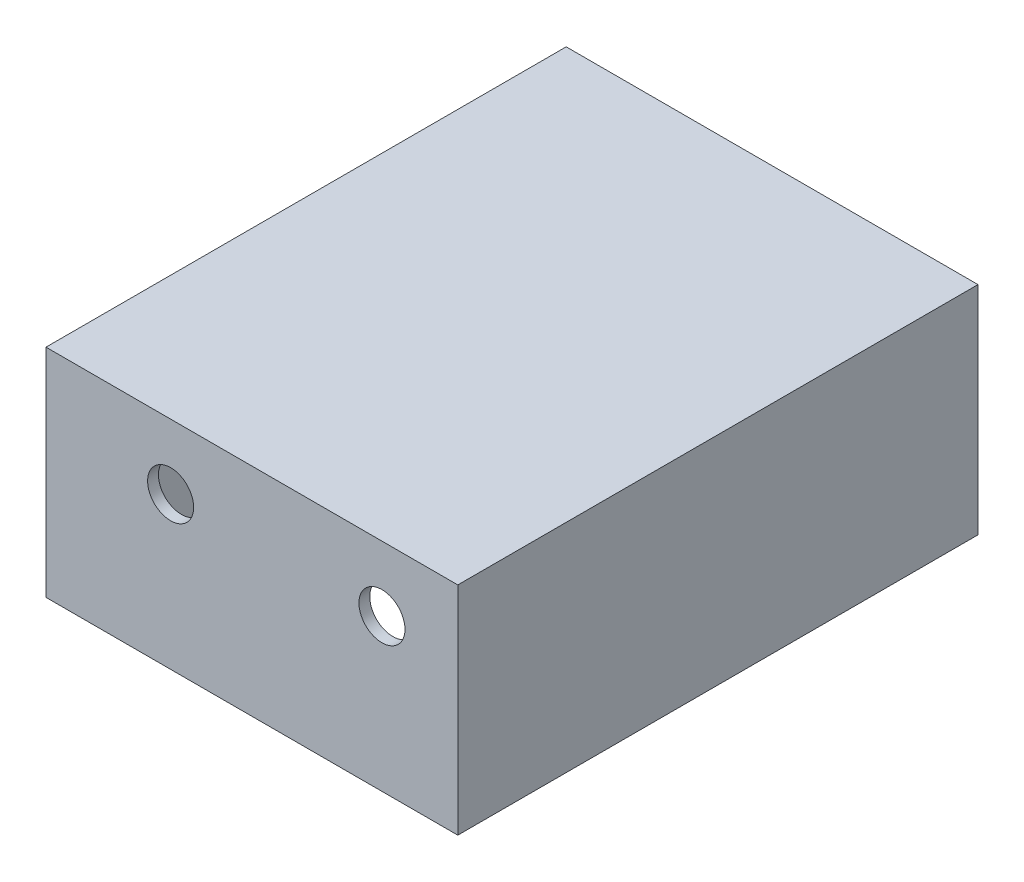
SolidWorks part; units mm, degrees
ref_plane "Front Plane" through (0, 0, 0) normal (0, 0, 1) x (1, 0, 0)
ref_plane "Top Plane" through (0, 0, 0) normal (0, 1, 0) x (1, 0, 0)
ref_plane "Right Plane" through (0, 0, 0) normal (1, 0, 0) x (0, 0, -1)
sketch "Sketch1" plane through (0, 0, 0) normal (0, 1, 0) x (1, 0, 0)
  line L1 (-38, 48) -> (38, 48)
  line L2 (-38, 48) -> (-38, -48)
  line L3 (-38, -48) -> (38, -48)
  line L4 (38, 48) -> (38, -48)
  line L5 (-38, 48) -> (38, -48) construction
  line L6 (-38, -48) -> (38, 48) construction
  point P0 (0, 0)
  dimension "D1" = 96
  dimension "D2" = 76
extrude "Boss-Extrude1" add sketch "Sketch1" along normal blind 40
sketch "Sketch2" plane through (0, 0, 0) normal (0, -1, 0) x (1, 0, 0)
  line L0 (38, -48) -> (-38, -48) construction
  line L1 (-36, -46) -> (36, -46)
  line L2 (-36, -46) -> (-36, 46)
  line L3 (-36, 46) -> (36, 46)
  line L4 (36, -46) -> (36, 46)
  line L5 (-36, -46) -> (36, 46) construction
  line L6 (-36, 46) -> (36, -46) construction
  line L7 (-38, -48) -> (-38, 48) construction
  point P0 (0, 0)
  dimension "D1" = 2
  dimension "D2" = 2
extrude "Cut-Extrude3" cut sketch "Sketch2" against normal offset from surface (38 mm away) 2 up to face at (0, 40, 0)
sketch "Sketch7" plane through (0, 0, 48) normal (0, 0, 1) x (1, 0, 0)
  line L1 (16.3135, 28) -> (-49983.6865, 28) construction
  line L4 (36, 38) -> (-36, 38) construction
  line L5 (36, 38) -> (36, 0) construction
  circle A0 centre (-15, 28) radius 4.25
  circle A1 centre (24, 28) radius 4.25
  dimension "D1" = 8.5
  dimension "D4" = 39
  dimension "D2" = 12
  dimension "D3" = 10
extrude "Cut-Extrude4" cut sketch "Sketch7" against normal up to next
sketch "Sketch10" plane through (0, 38, 0) normal (0, -1, 0) x (1, 0, 0)
  line L1 (36, -46) -> (36, 46) construction
  line L4 (5.5, 10) -> (-5.5, 10)
  line L5 (-36, -46) -> (36, -46) construction
  line L6 (5.5, 15) -> (-5.5, 15)
  line L7 (5.5, 10) -> (5.5, 15)
  line L8 (-5.5, 10) -> (-5.5, 15)
  dimension "D1" = 56
  dimension "D2" = 11
  dimension "D3" = 5
  dimension "D4" = 30.5
extrude "Boss-Extrude2" add sketch "Sketch10" along normal blind 15
fillet "Fillet2" radius 3 2 edges at (5.5, 30.5, 15) (-5.5, 30.5, 15)
sketch "Sketch11" plane through (0, 0, -46) normal (0, 0, 1) x (1, 0, 0)
  line L0 (36, 38) -> (36, 0) construction
  line L1 (25, 19) -> (19, 19)
  line L2 (25, 19) -> (25, 14)
  line L3 (25, 14) -> (19, 14)
  line L4 (19, 19) -> (19, 14)
  line L5 (25, 19) -> (19, 14) construction
  line L6 (25, 14) -> (19, 19) construction
  line L7 (-36, 38) -> (36, 38) construction
  point P0 (22, 16.5)
  dimension "D1" = 6
  dimension "D2" = 5
  dimension "D3" = 11
  dimension "D4" = 19
extrude "Cut-Extrude5" cut sketch "Sketch11" against normal up to next
sketch "Sketch12" plane through (0, 0, 10) normal (0, 0, -1) x (-1, 0, 0)
  line L0 (5.5, 23) -> (5.5, 38) construction
  line L1 (-5.5, 23) -> (-5.5, 38) construction
  line L2 (5.5, 23) -> (-5.5, 23) construction
  line L3 (5.5, 23) -> (5.5, 28)
  line L4 (-5.5, 23) -> (-5.5, 28)
  line L5 (5.5, 23) -> (-5.5, 23)
  line L6 (-5.5, 28) -> (5.5, 28)
  dimension "D1" = 5
extrude "Boss-Extrude3" add sketch "Sketch12" along normal blind 2
sketch "Sketch13" plane through (-38, 0, 0) normal (-1, 0, 0) x (0, 0, 1)
  line L0 (-48, 0) -> (48, 0) construction
  line L1 (-48, 40) -> (-48, 0) construction
  circle A0 centre (12, 14) radius 3.75
  dimension "D1" = 7.5
  dimension "D2" = 14
  dimension "D3" = 60
extrude "Cut-Extrude6" cut sketch "Sketch13" against normal up to next
sketch "Sketch15" plane through (0, 0, 0) normal (0, -1, 0) x (1, 0, 0)
  line L0 (36, -46) -> (36, 46) construction
  line L1 (36, 46) -> (-36, 46) construction
  line L2 (36, 36) -> (36, 46)
  line L3 (36, 46) -> (26, 46)
  line L4 (26, 46) -> (26, 36)
  line L5 (36, 36) -> (26, 36)
  circle A0 centre (31, 41) radius 1.25
  dimension "D5" = 2.5
  dimension "D1" = 10
  dimension "D2" = 10
  dimension "D3" = 5
  dimension "D4" = 5
extrude "Boss-Extrude4" add sketch "Sketch15" against normal blind 4
mirror "Mirror1" about plane through (0, 0, 0) normal (1, 0, 0) of "Boss-Extrude4"
mirror "Mirror2" about plane through (0, 0, 0) normal (0, 0, 1) of "Mirror1", "Boss-Extrude4"
sketch "Sketch17" plane through (0, 4, 0) normal (0, 1, 0) x (1, 0, 0)
  line L1 (34, -38) -> (28, -38)
  line L2 (34, -38) -> (34, -44)
  line L3 (34, -44) -> (28, -44)
  line L4 (28, -38) -> (28, -44)
  line L5 (34, -38) -> (28, -44) construction
  line L6 (34, -44) -> (28, -38) construction
  point P0 (31, -41)
  dimension "D1" = 6
  dimension "D2" = 6
extrude "Cut-Extrude7" cut sketch "Sketch17" against normal blind 2.5
mirror "Mirror3" about plane through (0, 0, 0) normal (1, 0, 0) of "Cut-Extrude7"
mirror "Mirror4" about plane through (0, 0, 0) normal (0, 0, 1) of "Mirror3", "Cut-Extrude7"
